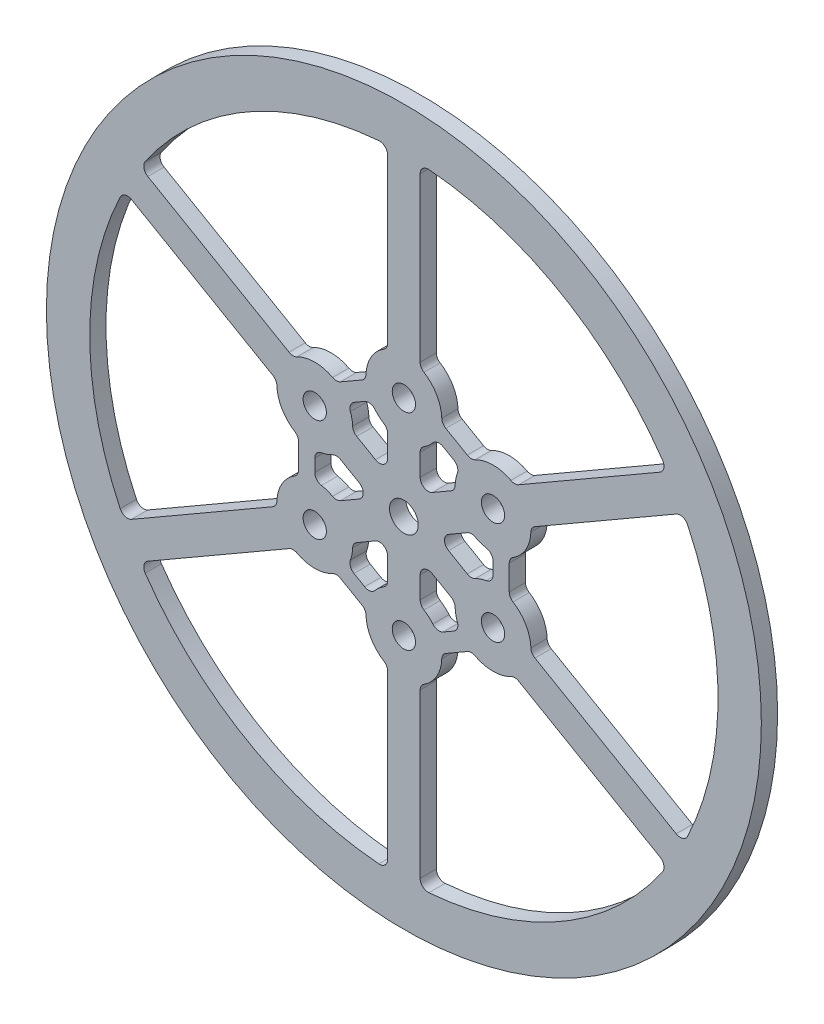
SolidWorks part; units mm, degrees
material "3.1325 (EN-AW 2017A)"
ref_plane "正面" through (0, 0, 0) normal (0, 0, 1) x (1, 0, 0)
ref_plane "平面" through (0, 0, 0) normal (0, 1, 0) x (1, 0, 0)
ref_plane "右側面" through (0, 0, 0) normal (1, 0, 0) x (0, 0, -1)
sketch "ｽｹｯﾁ1" plane through (0, 0, 0) normal (0, 0, 1) x (1, 0, 0)
  circle A0 centre (0, 0) radius 66
  circle A2 centre (0, 0) radius 19 construction
  point P4 (0, 19)
  point P8 (16.4545, 9.5)
  point P9 (16.4545, -9.5)
  point P10 (0, -19)
  point P11 (-16.4545, -9.5)
  point P12 (-16.4545, 9.5)
  point P13 (0, 0)
  dimension "D1" = 132
  dimension "D4" = 38
  dimension "D3" = 6
extrude "ﾎﾞｽ - 押し出し1" add sketch "ｽｹｯﾁ1" along normal mid plane 3
hole_wizard "M4 すきま穴1" positions "3Dｽｹｯﾁ1" profile "ｽｹｯﾁ2" hole size "M4" standard "JIS" end condition through all
sketch3d "3Dｽｹｯﾁ1"
  point P0 (0, 19, -1.5)
  point P2 (16.4545, 9.5, -1.5)
  point P4 (16.4545, -9.5, -1.5)
  point P6 (0, -19, -1.5)
  point P8 (-16.4545, -9.5, -1.5)
  point P10 (-16.4545, 9.5, -1.5)
sketch "ｽｹｯﾁ2" plane through (0, 19, -1.5) normal (1, 0, 0) x (0, 1, 0)
  line L0 (0, 0) -> (0, 3)
  line L1 (0, 3) -> (2.15, 3)
  line L2 (2.15, 3) -> (2.15, 0)
  line L5 (2.15, 0) -> (0, 0)
  line L11 (0, -6.35) -> (0, 107.95) construction
  dimension "通し穴の直径" = 4.3
  dimension "通し穴の深さ" = 3
hole_wizard "M5 すきま穴1" positions "3Dｽｹｯﾁ2" profile "ｽｹｯﾁ3" hole size "M5" standard "JIS" end condition through all
sketch3d "3Dｽｹｯﾁ2"
  point P0 (0, 0, 1.5)
sketch "ｽｹｯﾁ3" plane through (0, 0, 1.5) normal (1, 0, 0) x (0, -1, 0)
  line L0 (0, 0) -> (0, 3)
  line L1 (0, 3) -> (2.65, 3)
  line L2 (2.65, 3) -> (2.65, 0)
  line L5 (2.65, 0) -> (0, 0)
  line L11 (0, -6.35) -> (0, 107.95) construction
  dimension "通し穴の直径" = 5.3
  dimension "通し穴の深さ" = 3
sketch "ｽｹｯﾁ4" plane through (0, 0, 1.5) normal (0, 0, 1) x (1, 0, 0)
  line L0 (0, 19) -> (0, 70.5323) construction
  line L1 (3, 19) -> (3, 70.5323)
  line L2 (-3, 19) -> (-3, 70.5323)
  line L3 (14.9545, 12.0981) -> (59.5827, 37.8642)
  line L4 (17.9545, 6.9019) -> (62.5827, 32.6681)
  line L5 (17.9545, -6.9019) -> (62.5827, -32.6681)
  line L6 (14.9545, -12.0981) -> (59.5827, -37.8642)
  line L7 (3, -19) -> (3, -70.5323)
  line L8 (-3, -19) -> (-3, -70.5323)
  line L9 (-14.9545, -12.0981) -> (-59.5827, -37.8642)
  line L10 (-17.9545, -6.9019) -> (-62.5827, -32.6681)
  line L11 (-17.9545, 6.9019) -> (-62.5827, 32.6681)
  line L12 (-14.9545, 12.0981) -> (-59.5827, 37.8642)
  line L13 (0, 19) -> (-16.4545, 9.5) construction
  line L14 (-16.4545, 9.5) -> (-16.4545, -9.5) construction
  line L15 (-16.4545, -9.5) -> (0, -19) construction
  line L16 (0, -19) -> (16.4545, -9.5) construction
  line L17 (16.4545, -9.5) -> (16.4545, 9.5) construction
  line L18 (16.4545, 9.5) -> (0, 19) construction
  line L19 (0, 19) -> (0, -19) construction
  line L20 (-16.4545, -9.5) -> (16.4545, 9.5) construction
  line L21 (-16.4545, 9.5) -> (16.4545, -9.5) construction
  line L22 (19.4545, 11.2321) -> (0, 22.4641)
  line L23 (0, 22.4641) -> (-19.4545, 11.2321)
  line L24 (-19.4545, 11.2321) -> (-19.4545, -11.2321)
  line L25 (-19.4545, -11.2321) -> (0, -22.4641)
  line L26 (0, -22.4641) -> (19.4545, -11.2321)
  line L27 (19.4545, -11.2321) -> (19.4545, 11.2321)
  line L28 (16.4535, 9.4994) -> (0, 18.9988)
  line L29 (0, 18.9988) -> (-16.4535, 9.4994)
  line L30 (-16.4535, 9.4994) -> (-16.4535, -9.4994)
  line L31 (-16.4535, -9.4994) -> (0, -18.9988)
  line L32 (0, -18.9988) -> (16.4535, -9.4994)
  line L33 (16.4535, -9.4994) -> (16.4535, 9.4994)
  line L34 (-14.9545, -12.0981) -> (17.9545, 6.9019)
  line L35 (-3, 19) -> (-3, -19)
  line L36 (-17.9545, 6.9019) -> (14.9545, -12.0981)
  line L37 (-17.9545, -6.9019) -> (14.9545, 12.0981)
  line L38 (3, 19) -> (3, -19)
  line L39 (-14.9545, 12.0981) -> (17.9545, -6.9019)
  circle A1 centre (0, 19) radius 7
  circle A2 centre (0, 0) radius 58
  circle A3 centre (0, 0) radius 58
  circle A5 centre (16.4545, 9.5) radius 7
  circle A6 centre (16.4545, -9.5) radius 7
  circle A7 centre (0, -19) radius 7
  circle A8 centre (-16.4545, -9.5) radius 7
  circle A9 centre (-16.4545, 9.5) radius 7
  circle A10 centre (0, 0) radius 8
  point P45 (0, 0)
  dimension "D2" = 14
  dimension "D3" = 3
  dimension "D6" = 16
  dimension "D7" = 16
  dimension "D1" = 8
  dimension "D4" = 3
  dimension "D8" = 3
  dimension "D9" = 0.001
  dimension "D10" = 3
  dimension "D11" = 3
  dimension "D5" = 6
extrude "ｶｯﾄ - 押し出し1" cut sketch "ｽｹｯﾁ4" against normal through all contours A9 L23 A1 L2 A3 L12 | A9 L11 A3 L10 A8 L24 | A10 L36 A9 L30 A8 L37 | A10 L35 A1 L29 A9 L39 | A10 L37 A5 L28 A1 L38 | A10 L39 A6 L33 A5 L34 | A10 L38 A7 L32 A6 L36 | A10 L34 A8 L31 A7 L35 | L34 A10 L35 | L36 A10 L37 | L35 A10 L39 | L37 A10 L38 | L39 A10 L34 | L38 A10 L36 | A8 L9 A3 L8 A7 L25 | A7 L7 A3 L6 A6 L26 | A6 L5 A3 L4 A5 L27 | A5 L3 A3 L1 A1 L22
fillet "ﾌｨﾚｯﾄ1" radius 1.5 66 edges at (-12.4773, -15.2604, 0) (-6.9772, -18.4358, 0) (-3, -25.3246, 0) (-3, -57.9224, 0) (-48.6622, -31.5593, 0) (-20.4317, -15.2604, 0) (12.4773, 3.7396, 0) (16.4535, -2.5, 0) (12.4773, -3.7396, 0) (6, 0, 0) (6.0617, 15.4991, 0) (10.3918, 12.9991, 0) (9.4773, 8.9358, 0) (3, 5.1962, 0) (3, 12.6754, 0) (-3, -12.6754, 0) (-6.0617, -15.4991, 0) (-10.3918, -12.9991, 0) (-9.4773, -8.9358, 0) (-3, -5.1962, 0) (-16.4535, -2.5, 0) (-16.4535, 2.5, 0) (-12.4773, 3.7396, 0) (-6, 0, 0) (-12.4773, -3.7396, 0) (-10.3918, 12.9991, 0) (-6.0617, 15.4991, 0) (-3, 12.6754, 0) (-3, 5.1962, 0) (-9.4773, 8.9358, 0) (6.9772, -18.4358, 0) (12.4773, -15.2604, 0) (20.4317, -15.2604, 0) (48.6622, -31.5593, 0) (3, -57.9224, 0) (3, -25.3246, 0) (-20.4317, 15.2604, 0) (-48.6622, 31.5593, 0) (-3, 57.9224, 0) (-3, 25.3246, 0) (-6.9772, 18.4358, 0) (-12.4773, 15.2604, 0) (19.4545, -3.1754, 0) (19.4545, 3.1754, 0) (23.4317, 10.0642, 0) (51.6622, 26.3631, 0) (51.6622, -26.3631, 0) (23.4317, -10.0642, 0) (12.4773, 15.2604, 0) (6.9772, 18.4358, 0) (3, 25.3246, 0) (3, 57.9224, 0) (48.6622, 31.5593, 0) (20.4317, 15.2604, 0) (-19.4545, 3.1754, 0) (-19.4545, -3.1754, 0) (-23.4317, -10.0642, 0) (-51.6622, -26.3631, 0) (-51.6622, 26.3631, 0) (-23.4317, 10.0642, 0) (9.4773, -8.9358, 0) (10.3918, -12.9991, 0) (6.0617, -15.4991, 0) (3, -12.6754, 0) (3, -5.1962, 0) (16.4535, 2.5, 0)
